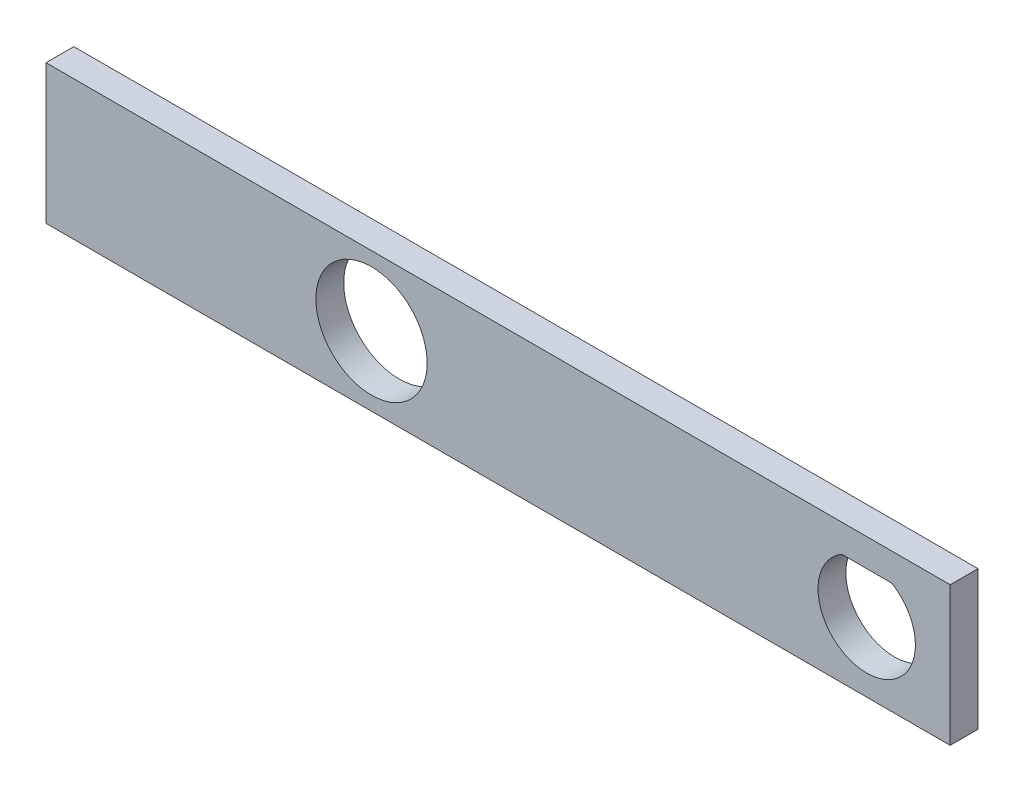
SolidWorks part; units mm, degrees
ref_plane "Front Plane" through (0, 0, 0) normal (0, 0, 1) x (1, 0, 0)
ref_plane "Top Plane" through (0, 0, 0) normal (0, 1, 0) x (1, 0, 0)
ref_plane "Right Plane" through (0, 0, 0) normal (1, 0, 0) x (0, 0, -1)
sketch "Sketch1" plane through (0, 0, 0) normal (0, 0, 1) x (1, 0, 0)
  line L0 (-23.4, 0) -> (0, 0) construction
  line L1 (-23.4, 5) -> (41.6, 5)
  line L2 (-23.4, 5) -> (-23.4, -5)
  line L3 (-23.4, -5) -> (41.6, -5)
  line L4 (41.6, 5) -> (41.6, -5)
  line L5 (33.7972, 3) -> (37.4028, 3)
  circle A0 centre (0, 0) radius 4
  arc A1 (33.7972, 3) -> (37.4028, 3) centre (35.6, 0) ccw
  dimension "D1" = 8
  dimension "D5" = 7
  dimension "D2" = 65
  dimension "D3" = 10
  dimension "D4" = 23.4
  dimension "D6" = 3
  dimension "D7" = 6
extrude "Boss-Extrude2" add sketch "Sketch1" along normal blind 2
